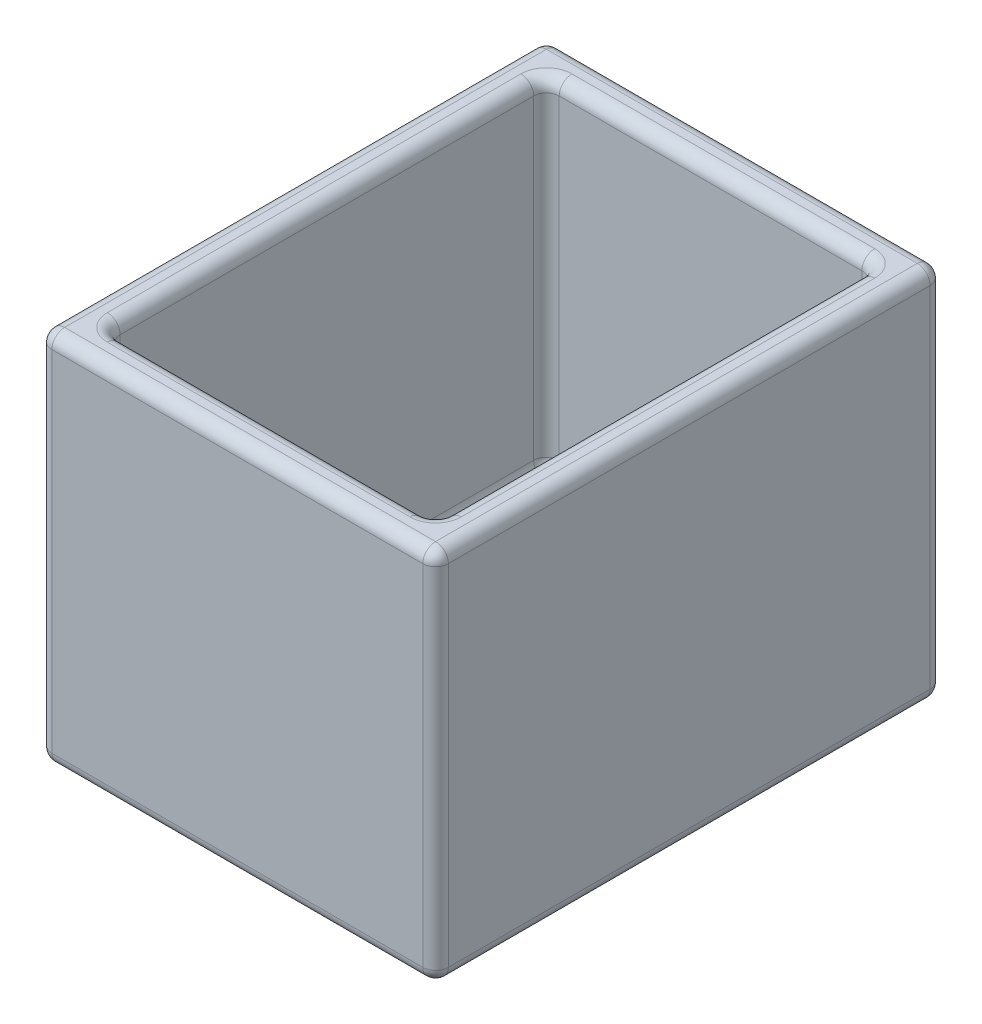
SolidWorks part; units mm, degrees
ref_plane "Front Plane" through (0, 0, 0) normal (0, 0, 1) x (1, 0, 0)
ref_plane "Top Plane" through (0, 0, 0) normal (0, 1, 0) x (1, 0, 0)
ref_plane "Right Plane" through (0, 0, 0) normal (1, 0, 0) x (0, 0, -1)
sketch "Sketch1" plane through (0, 0, 0) normal (0, 1, 0) x (1, 0, 0)
  line L1 (19.25, -25.75) -> (-19.25, -25.75)
  line L2 (19.25, -25.75) -> (19.25, 25.75)
  line L3 (19.25, 25.75) -> (-19.25, 25.75)
  line L4 (-19.25, -25.75) -> (-19.25, 25.75)
  line L5 (19.25, -25.75) -> (-19.25, 25.75) construction
  line L6 (19.25, 25.75) -> (-19.25, -25.75) construction
  point P0 (0, 0)
  dimension "D1" = 51.5
  dimension "D2" = 38.5
extrude "Boss-Extrude1" add sketch "Sketch1" along normal blind 40
shell "Shell1" thickness 4
sketch "Sketch2" plane through (0, 0, -29.75) normal (0, 0, -1) x (-1, 0, 0)
  line L3 (-23.25, -4) -> (23.25, -4) construction
  circle A1 centre (0, 6) radius 2.5
  dimension "D1" = 5
  dimension "D2" = 10
extrude "Cut-Extrude3" cut sketch "Sketch2" against normal up to surface (4 mm away) from surface at 0 up to face at (0, 20, -25.75) starting at face at (0, 18, -29.75)
sketch "Sketch3" plane through (0, 0, 0) normal (0, 1, 0) x (1, 0, 0)
  line L0 (0, 25.75) -> (0, -25.75) construction
  line L1 (19.25, 25.75) -> (-19.25, 25.75) construction
  line L2 (-19.25, -25.75) -> (19.25, -25.75) construction
  line L6 (-19.25, 0) -> (19.25, 0) construction
  line L7 (-19.25, 25.75) -> (-19.25, -25.75) construction
  line L8 (19.25, -25.75) -> (19.25, 25.75) construction
fillet "Fillet2" radius 1.5 24 edges at (23.25, 18, -29.75) (23.25, 18, 29.75) (-23.25, 18, 29.75) (0, -4, 29.75) (23.25, -4, 0) (-23.25, -4, 0) (-23.25, 18, -29.75) (0, -4, -29.75) (0, 40, -29.75) (0, 40, -25.75) (-23.25, 40, 0) (-19.25, 40, 0) (0, 40, 29.75) (0, 40, 25.75) (19.25, 40, 0) (23.25, 40, 0) (-19.25, 20, 25.75) (19.25, 20, -25.75) (-19.25, 20, -25.75) (19.25, 20, 25.75) (19.25, 0, 0) (0, 0, 25.75) (-19.25, 0, 0) (0, 0, -25.75)
sketch "Sketch5" plane through (0, 0, 0) normal (0, 1, 0) x (1, 0, 0)
  line L0 (-19.25, -25.75) -> (19.25, -25.75) construction
  line L2 (-19.25, 25.75) -> (-19.25, -25.75) construction
  circle A0 centre (-4.25, -16.25) radius 2
  dimension "D1" = 4
  dimension "D2" = 9.5
  dimension "D3" = 15
extrude "Cut-Extrude4" cut sketch "Sketch5" against normal through all
